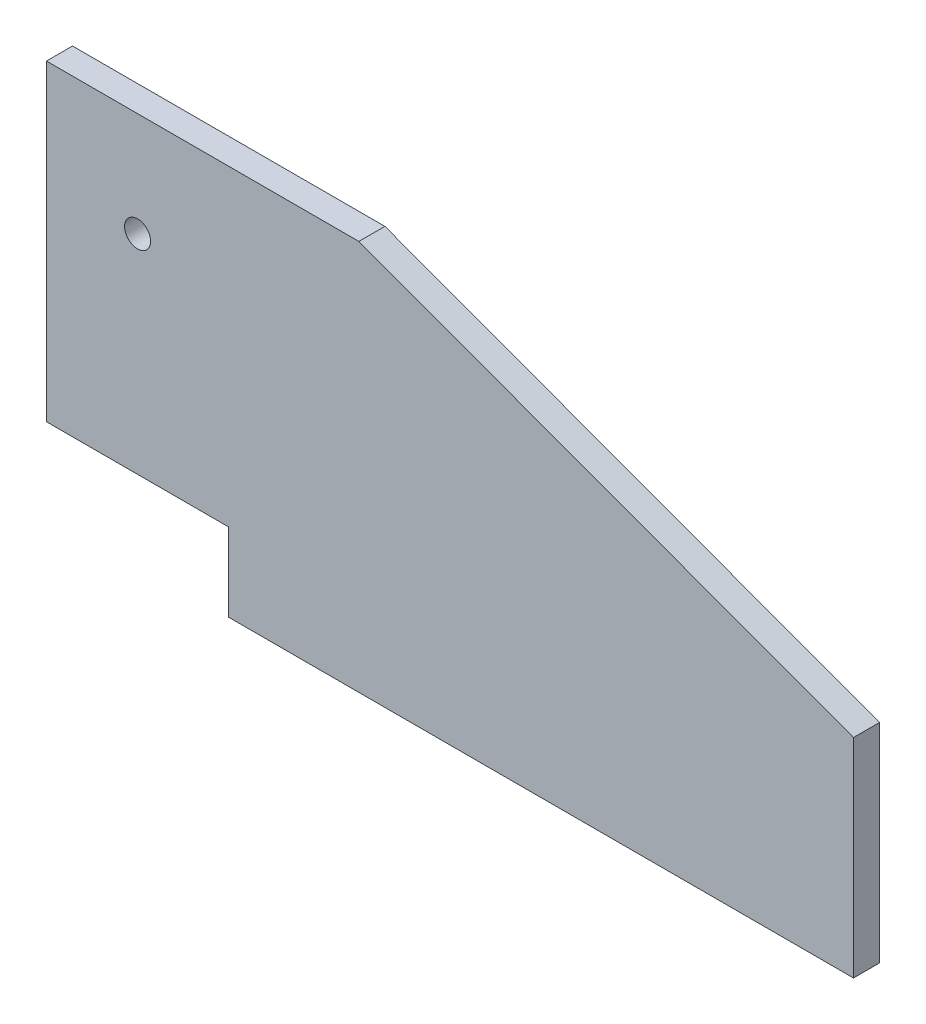
SolidWorks part; units mm, degrees
material "Pine"
ref_plane "Front Plane" through (0, 0, 0) normal (0, 0, 1) x (1, 0, 0)
ref_plane "Top Plane" through (0, 0, 0) normal (0, 1, 0) x (1, 0, 0)
ref_plane "Right Plane" through (0, 0, 0) normal (1, 0, 0) x (0, 0, -1)
sketch "Sketch1" plane through (0, 0, 0) normal (0, 0, 1) x (1, 0, 0)
  line L8 (0, 38.1438) -> (-88.9, 38.1438)
  line L9 (-88.9, 38.1438) -> (-88.9, 190.5438)
  line L10 (-88.9, 190.5438) -> (63.5, 190.5438)
  line L11 (63.5, 190.5438) -> (304.8, 101.6)
  line L12 (304.8, 101.6) -> (304.8, 0)
  line L13 (304.8, 0) -> (0, 0)
  line L15 (0, 0) -> (0, 38.1438)
  dimension "D1" = 88.9
  dimension "D2" = 38.1438
  dimension "D3" = 152.4
  dimension "D4" = 304.8
  dimension "D5" = 101.6
  dimension "D6" = 152.4
extrude "Boss-Extrude1" add sketch "Sketch1" along normal mid plane 12.7
hole_wizard "1/2 (0.5) Diameter Hole1" positions "3DSketch1" profile "Sketch2" hole size "1/2" standard "ANSI Inch" end condition through all
sketch3d "3DSketch1"
  line L0 (-44.45, 38.1438, 6.35) -> (-44.45, 190.5438, 6.35)
  line L1 (0, 38.1438, 6.35) -> (-88.9, 38.1438, 6.35) construction
  line L2 (-88.9, 190.5438, 6.35) -> (63.5, 190.5438, 6.35) construction
  point P9 (-44.45, 139.7438, 6.35)
  point P12 (0, 0, 0)
  point P13 (0, 0, 0)
  dimension "D1" = 101.6
sketch "Sketch2" plane through (-44.45, 139.7438, 6.35) normal (1, 0, 0) x (0, -1, 0)
  line L0 (0, 0) -> (0, 12.7)
  line L1 (0, 12.7) -> (6.35, 12.7)
  line L2 (6.35, 12.7) -> (6.35, 0)
  line L5 (6.35, 0) -> (0, 0)
  line L11 (0, -6.35) -> (0, 107.95) construction
  dimension "Thru Hole Dia." = 12.7
  dimension "Thru Hole Depth" = 12.7
